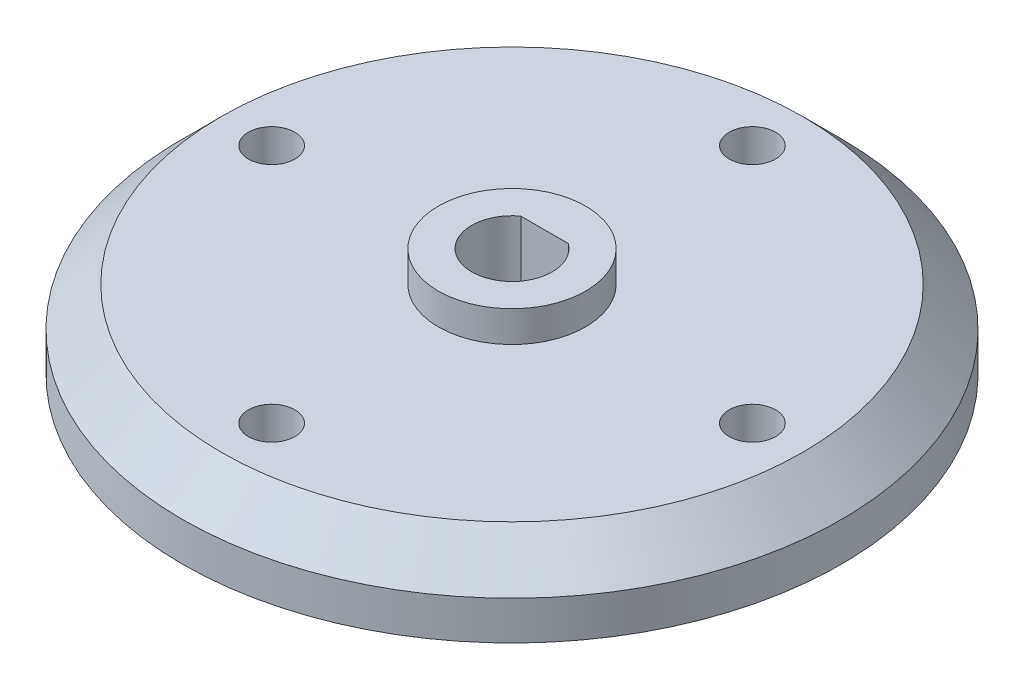
SolidWorks part; units mm, degrees
ref_plane "Front Plane" through (0, 0, 0) normal (0, 0, 1) x (1, 0, 0)
ref_plane "Top Plane" through (0, 0, 0) normal (0, 1, 0) x (1, 0, 0)
ref_plane "Right Plane" through (0, 0, 0) normal (1, 0, 0) x (0, 0, -1)
sketch "Sketch1" plane through (0, 0, 0) normal (0, 1, 0) x (1, 0, 0)
  line L0 (-1.533, 2.1) -> (1.533, 2.1)
  line L1 (0, 0) -> (0, -2.6) construction
  circle A0 centre (0, 0) radius 21.25
  circle A1 centre (0, 0) radius 15.5 construction
  circle A2 centre (0, 0) radius 2.6 construction
  circle A3 centre (0, 15.5) radius 1.5
  circle A4 centre (15.5, 0) radius 1.5
  circle A5 centre (0, -15.5) radius 1.5
  circle A6 centre (-15.5, 0) radius 1.5
  arc A7 (-1.533, 2.1) -> (1.533, 2.1) centre (0, 0) ccw
  dimension "D1" = 5.2
  dimension "D2" = 31
  dimension "D3" = 42.5
  dimension "D4" = 3
  dimension "D5" = 4.7
extrude "Boss-Extrude1" add sketch "Sketch1" along normal blind 5
chamfer "Chamfer1" distance 2.5 angle 45 1 edges at (0, 5, 21.25)
sketch "Sketch2" plane through (0, 5, 0) normal (0, 1, 0) x (1, 0, 0)
  line L1 (1.533, 2.1) -> (-1.533, 2.1)
  line L2 (1.533, 2.1) -> (-1.533, 2.1)
  circle A0 centre (0, 0) radius 4.75
  arc A1 (-1.533, 2.1) -> (1.533, 2.1) centre (0, 0) ccw
  arc A2 (-1.533, 2.1) -> (1.533, 2.1) centre (0, 0) ccw
  dimension "D2" = 9.5
  dimension "D1" = 0
extrude "Boss-Extrude2" add sketch "Sketch2" along normal blind 2
